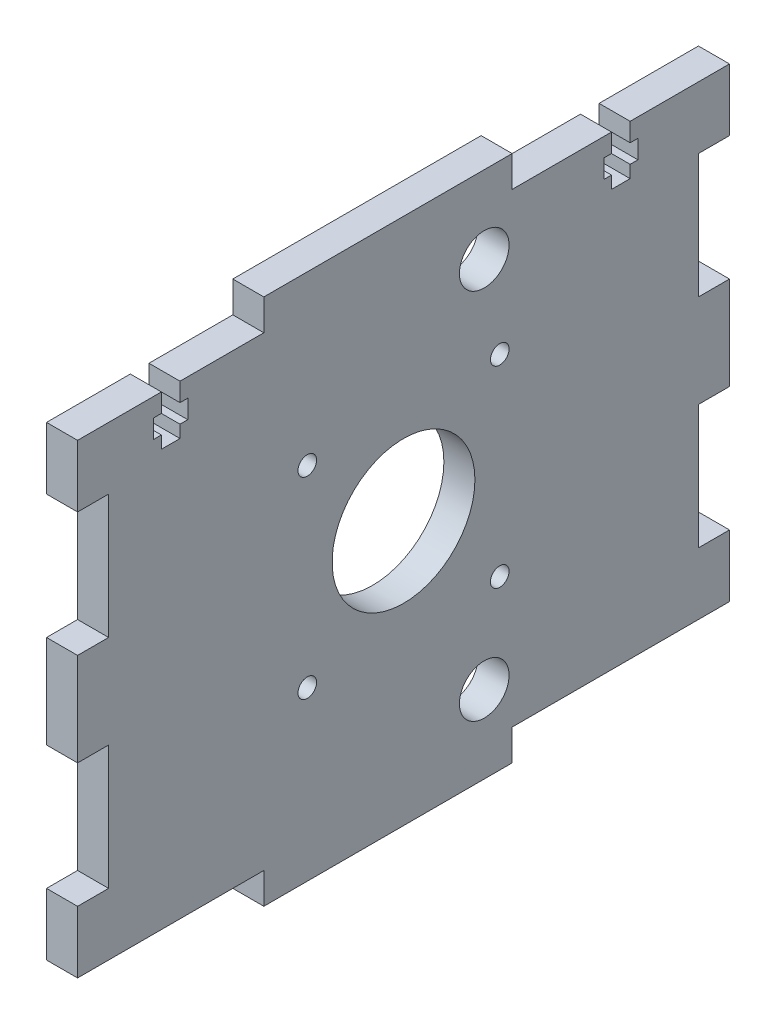
SolidWorks part; units mm, degrees
ref_plane "前视基准面" through (0, 0, 0) normal (0, 0, 1) x (1, 0, 0)
ref_plane "上视基准面" through (0, 0, 0) normal (0, 1, 0) x (1, 0, 0)
ref_plane "右视基准面" through (0, 0, 0) normal (1, 0, 0) x (0, 0, -1)
sketch "草图1" plane through (0, 0, 0) normal (1, 0, 0) x (0, 0, -1)
  line L0 (-75, 75) -> (-88.5, 75)
  line L1 (0, 0) -> (-35, 0)
  line L2 (0, 0) -> (0, 10)
  line L3 (0, 75) -> (-16, 75)
  line L4 (-105, 0) -> (-105, 10)
  line L5 (-52.5, 96.4418) -> (-52.5, -28.6228) construction
  line L6 (-75, 0) -> (-75, -5)
  line L7 (-75, -5) -> (-35, -5)
  line L8 (-35, 0) -> (-35, -5)
  line L9 (-105, 65) -> (-105, 75)
  line L10 (-75, 75) -> (-75, 80)
  line L11 (-75, 80) -> (-35, 80)
  line L12 (-35, 75) -> (-35, 80)
  line L13 (0, 65) -> (-5, 65)
  line L14 (-39.5, 77.0793) -> (-39.5, 3.0891) construction
  line L15 (0, 45) -> (-5, 45)
  line L16 (-5, 65) -> (-5, 45)
  line L17 (0, 30) -> (-5, 30)
  line L18 (-16, 75) -> (-16, 72)
  line L19 (0, 10) -> (-5, 10)
  line L20 (-5, 30) -> (-5, 10)
  line L21 (-105, 30) -> (-100, 30)
  line L22 (0, 65) -> (0, 75)
  line L23 (-105, 10) -> (-100, 10)
  line L24 (-100, 30) -> (-100, 10)
  line L25 (-105, 65) -> (-100, 65)
  line L26 (-16, 72) -> (-14.75, 72)
  line L27 (-105, 45) -> (-100, 45)
  line L28 (-100, 65) -> (-100, 45)
  line L29 (-105, 30) -> (-105, 45)
  line L30 (0, 30) -> (0, 45)
  line L31 (-75, 0) -> (-105, 0)
  line L32 (-14.75, 72) -> (-14.75, 69)
  line L33 (-14.75, 69) -> (-16, 69)
  line L34 (-16, 69) -> (-16, 67)
  line L35 (-16, 67) -> (-19, 67)
  line L36 (-19, 67) -> (-19, 69)
  line L37 (-19, 69) -> (-20.25, 69)
  line L38 (-20.25, 69) -> (-20.25, 72)
  line L39 (-20.25, 72) -> (-19, 72)
  line L40 (-19, 72) -> (-19, 75)
  line L41 (-19, 75) -> (-35, 75)
  line L42 (-88.5, 75) -> (-88.5, 72)
  line L43 (-88.5, 72) -> (-87.25, 72)
  line L44 (-87.25, 72) -> (-87.25, 69)
  line L45 (-87.25, 69) -> (-88.5, 69)
  line L46 (-88.5, 69) -> (-88.5, 67)
  line L47 (-88.5, 67) -> (-91.5, 67)
  line L48 (-91.5, 67) -> (-91.5, 69)
  line L49 (-91.5, 69) -> (-92.75, 69)
  line L50 (-92.75, 69) -> (-92.75, 72)
  line L51 (-92.75, 72) -> (-91.5, 72)
  line L52 (-91.5, 72) -> (-91.5, 75)
  line L53 (-91.5, 75) -> (-105, 75)
  circle A0 centre (-52.5, 37.5) radius 11.5
  circle A1 centre (-68, 53) radius 1.5
  circle A2 centre (-37, 53) radius 1.5
  circle A3 centre (-37, 22) radius 1.5
  circle A4 centre (-68, 22) radius 1.5
  circle A5 centre (-39.5, 67.5) radius 4
  circle A6 centre (-39.5, 7.5) radius 4
  dimension "D28" = 23
  dimension "D34" = 13
  dimension "D35" = 8
  dimension "D36" = 8
  dimension "D1" = 105
  dimension "D2" = 75
  dimension "D3" = 40
  dimension "D4" = 40
  dimension "D5" = 5
  dimension "D6" = 5
  dimension "D7" = 5
  dimension "D8" = 5
  dimension "D9" = 5
  dimension "D10" = 5
  dimension "D11" = 20
  dimension "D12" = 20
  dimension "D13" = 20
  dimension "D14" = 20
  dimension "D15" = 35
  dimension "D16" = 35
  dimension "D17" = 10
  dimension "D18" = 10
  dimension "D19" = 10
  dimension "D20" = 10
  dimension "D21" = 15.5
  dimension "D22" = 15.5
  dimension "D23" = 15.5
  dimension "D24" = 15.5
  dimension "D25" = 31
  dimension "D26" = 15.5
  dimension "D27" = 15.5
  dimension "D29" = 52.5
  dimension "D30" = 0
  dimension "D31" = 15.5
  dimension "D32" = 15.5
  dimension "D33" = 37.5
  dimension "D37" = 60
  dimension "D38" = 7.5
  dimension "D39" = 30
  dimension "D40" = 3
  dimension "D41" = 5.5
  dimension "D42" = 3
  dimension "D43" = 1.25
  dimension "D44" = 1.25
  dimension "D45" = 16
  dimension "D46" = 3
  dimension "D47" = 5.5
  dimension "D48" = 3
  dimension "D49" = 1.25
  dimension "D50" = 1.25
  dimension "D51" = 13.5
extrude "凸台-拉伸1" add sketch "草图1" along normal blind 5
